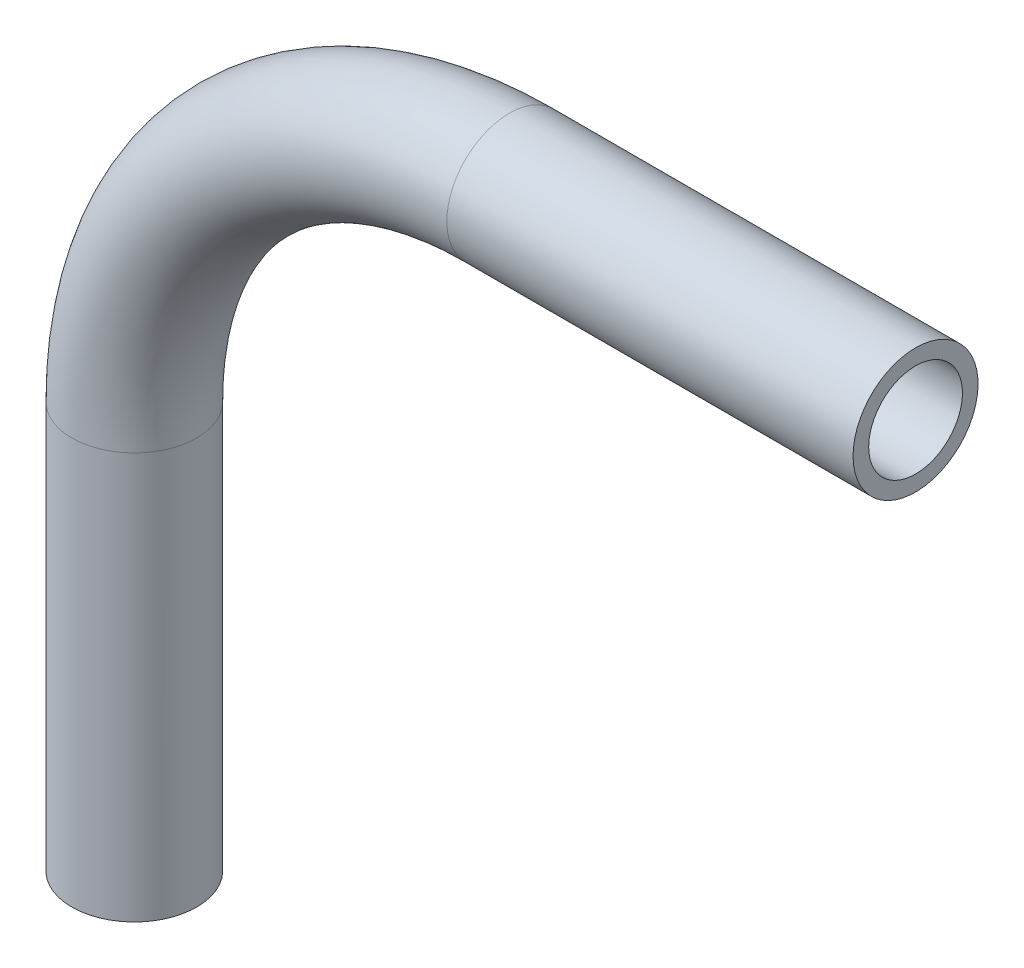
SolidWorks part; units mm, degrees
ref_plane "Front Plane" through (0, 0, 0) normal (0, 0, 1) x (1, 0, 0)
ref_plane "Top Plane" through (0, 0, 0) normal (0, 1, 0) x (1, 0, 0)
ref_plane "Right Plane" through (0, 0, 0) normal (1, 0, 0) x (0, 0, -1)
sketch "Sketch1" plane through (0, 0, 0) normal (0, 0, 1) x (1, 0, 0)
  line L0 (0, 0) -> (0, 26)
  line L1 (24, 50) -> (50, 50)
  arc A0 (0, 26) -> (24, 50) centre (24, 26) cw
  point P6 (0, 50)
  dimension "D3" = 24
  dimension "D1" = 50
  dimension "D2" = 50
  dimension "D4" = 90
sketch "Sketch2" plane through (0, 0, 0) normal (0, 1, 0) x (1, 0, 0)
  circle A0 centre (0, 0) radius 4
  circle A1 centre (0, 0) radius 3
  dimension "D1" = 6
  dimension "D2" = 8
sweep "Sweep1" add profiles "Sketch2" path "Sketch1"
